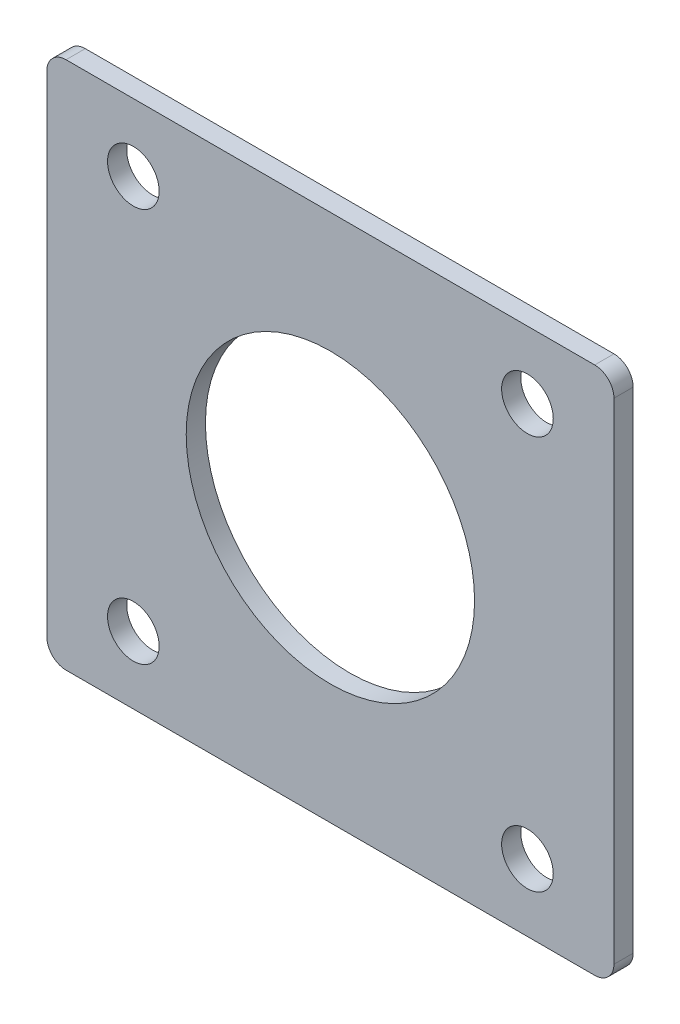
SolidWorks part; units mm, degrees
ref_plane "Front Plane" through (0, 0, 0) normal (0, 0, 1) x (1, 0, 0)
ref_plane "Top Plane" through (0, 0, 0) normal (0, 1, 0) x (1, 0, 0)
ref_plane "Right Plane" through (0, 0, 0) normal (1, 0, 0) x (0, 0, -1)
sketch "Sketch1" plane through (0, 0, 0) normal (0, 0, 1) x (1, 0, 0)
  line L0 (93.6625, -80.9625) -> (93.6625, -49.2125) construction
  line L1 (-93.6625, 87.3125) -> (93.6625, 87.3125)
  line L2 (-93.6625, 87.3125) -> (-93.6625, -87.3125)
  line L3 (-93.6625, -87.3125) -> (93.6625, -87.3125)
  line L4 (93.6625, 87.3125) -> (93.6625, -87.3125)
  line L5 (-93.6625, 80.9625) -> (-93.6625, 49.2125) construction
  line L6 (87.3125, 87.3125) -> (-87.3125, 87.3125) construction
  line L7 (-87.3125, -87.3125) -> (87.3125, -87.3125) construction
  circle A0 centre (-65.0875, 65.0875) radius 8.5328
  circle A1 centre (65.0875, 65.0875) radius 8.5328
  circle A2 centre (65.0875, -65.0875) radius 8.5328
  circle A3 centre (-65.0875, -65.0875) radius 8.5328
  circle A4 centre (-65.0875, 65.0875) radius 8.5328 construction
  circle A5 centre (65.0875, 65.0875) radius 8.5328 construction
  circle A6 centre (-65.0875, -65.0875) radius 8.5328 construction
  circle A7 centre (65.0875, -65.0875) radius 8.5328 construction
  circle A8 centre (0, 0) radius 47.625
  circle A9 centre (0, 0) radius 47.625 construction
extrude "Extrude1" add sketch "Sketch1" along normal blind 6.35
fillet "Fillet1" radius 6.35 4 edges at (-93.6625, -87.3125, 3.175) (-93.6625, 87.3125, 3.175) (93.6625, 87.3125, 3.175) (93.6625, -87.3125, 3.175)
